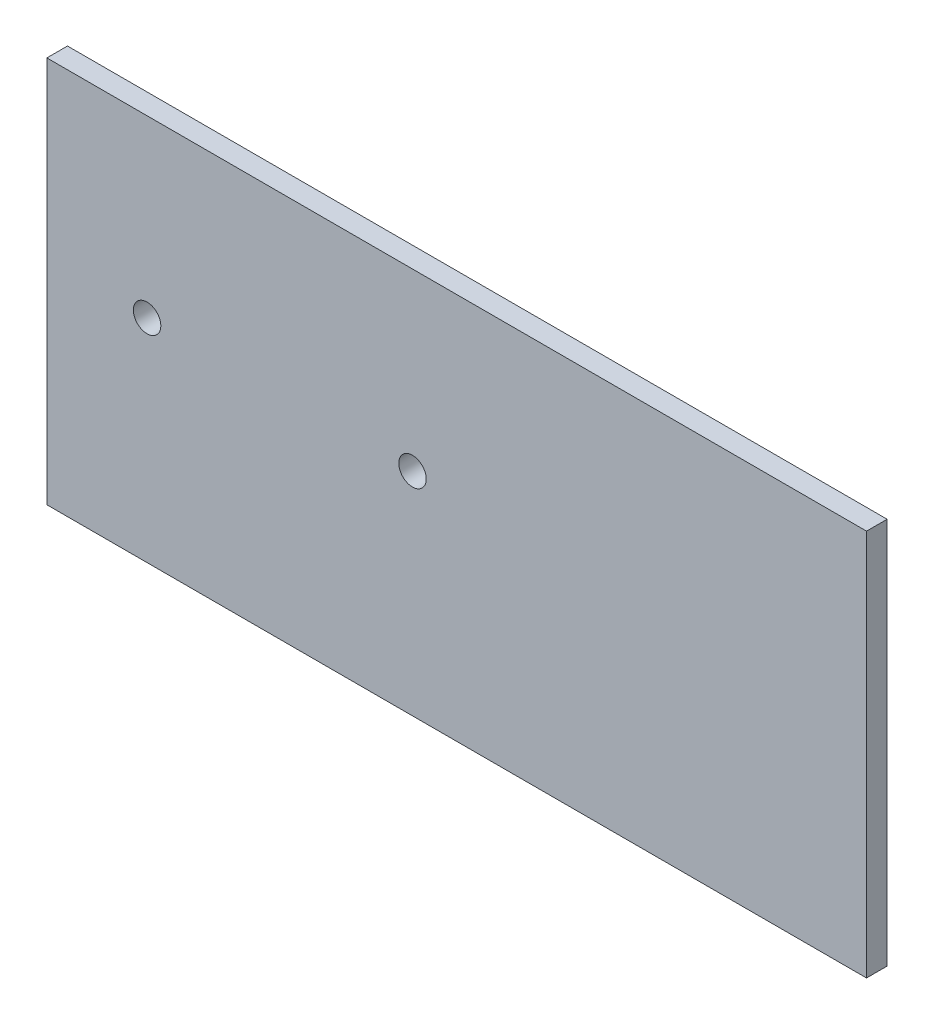
SolidWorks part; units mm, degrees
ref_plane "Front Plane" through (0, 0, 0) normal (0, 0, 1) x (1, 0, 0)
ref_plane "Top Plane" through (0, 0, 0) normal (0, 1, 0) x (1, 0, 0)
ref_plane "Right Plane" through (0, 0, 0) normal (1, 0, 0) x (0, 0, -1)
sketch "Sketch1" plane through (0, 0, 0) normal (0, 0, 1) x (1, 0, 0)
  line L0 (-67.7616, 0) -> (-29.1238, 0)
  line L2 (-82.3509, 25.4889) -> (36.9766, 25.4889)
  line L3 (-82.3509, 25.4889) -> (-82.3509, -30.8533)
  line L4 (-82.3509, -30.8533) -> (36.9766, -30.8533)
  line L5 (36.9766, 25.4889) -> (36.9766, -30.8533)
  circle A0 centre (-67.7616, 0) radius 2
  circle A1 centre (-29.1238, 0) radius 2
extrude "Boss-Extrude1" add sketch "Sketch1" along normal blind 3 contours L2 L5 L4 L3 | A1 | A0
